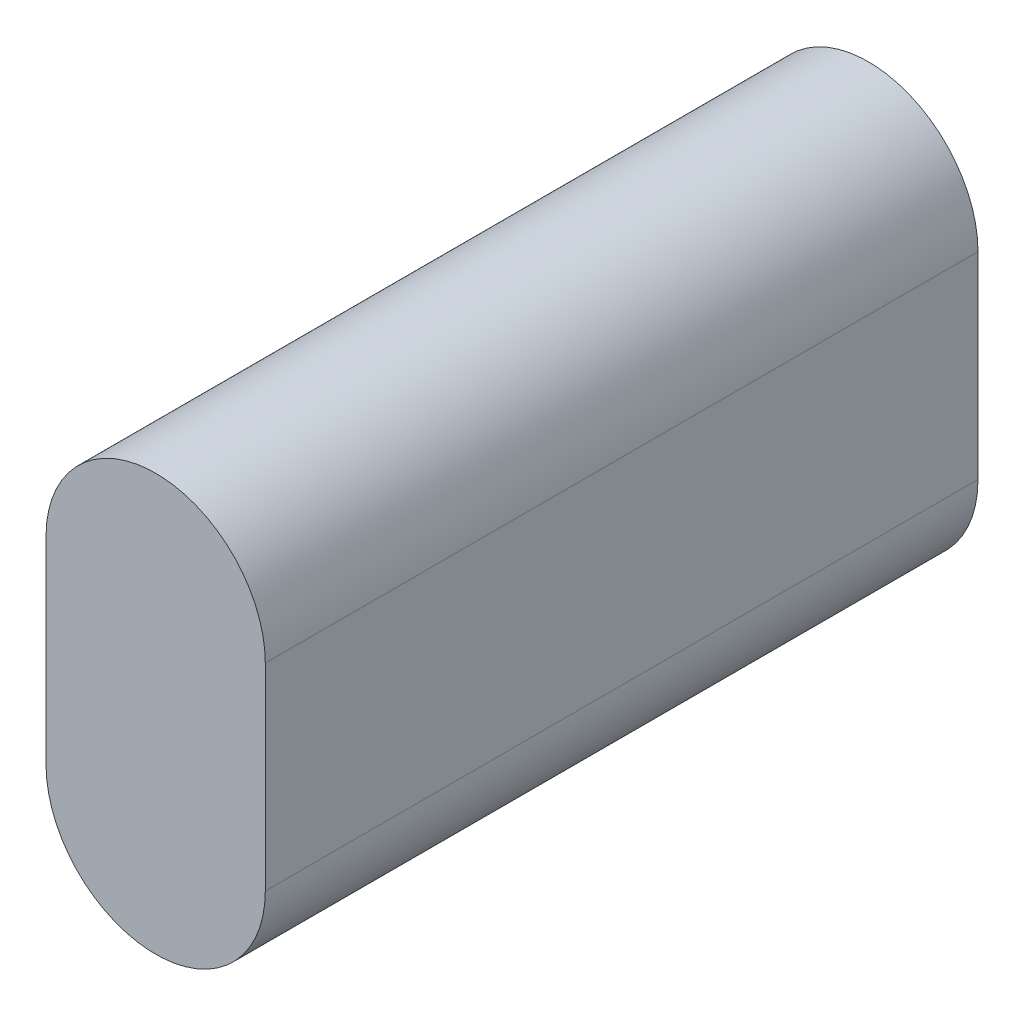
SolidWorks part; units mm, degrees
ref_plane "前视基准面" through (0, 0, 0) normal (0, 0, 1) x (1, 0, 0)
ref_plane "上视基准面" through (0, 0, 0) normal (0, 1, 0) x (1, 0, 0)
ref_plane "右视基准面" through (0, 0, 0) normal (1, 0, 0) x (0, 0, -1)
sketch "草图1" plane through (0, 0, 0) normal (0, 0, 1) x (1, 0, 0)
  line L2 (10, 9) -> (10, -9)
  line L4 (-10, -9) -> (-10, 9)
  arc A0 (10, 9) -> (-10, 9) centre (0, 9) ccw
  arc A1 (-10, -9) -> (10, -9) centre (0, -9) ccw
extrude "凸台-拉伸1" add sketch "草图1" along normal blind 65
